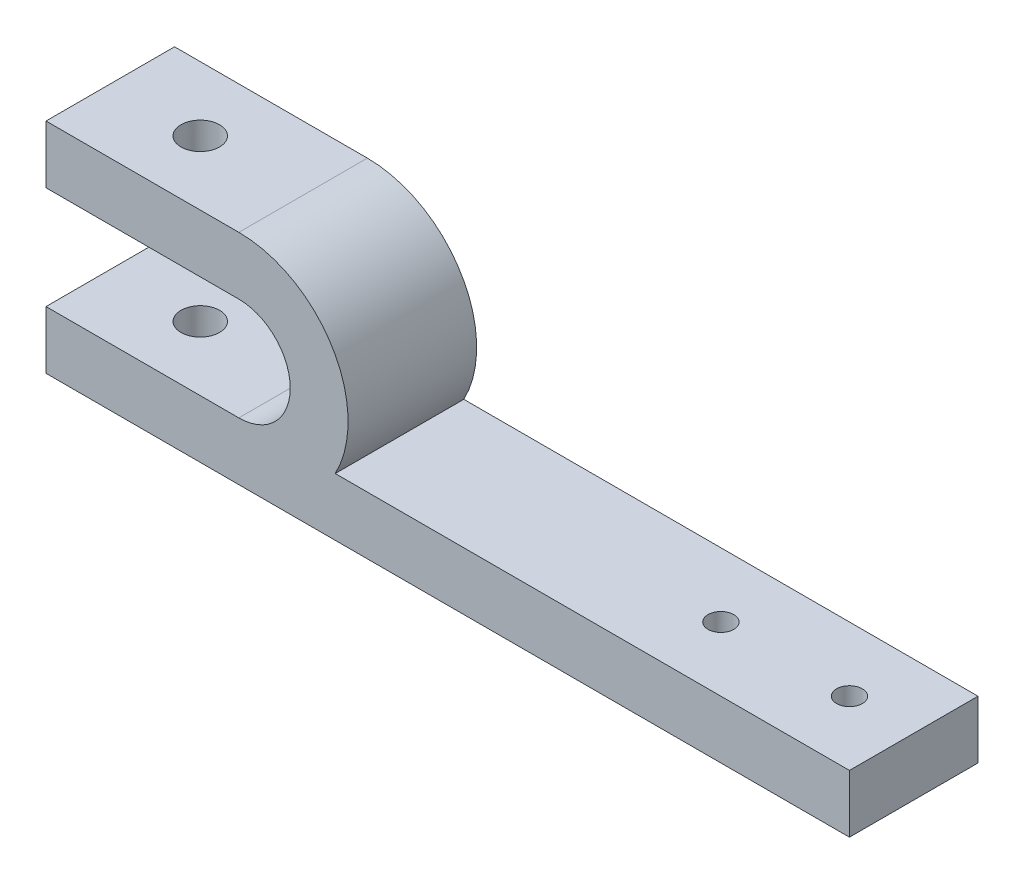
SolidWorks part; units mm, degrees
ref_plane "Alzado" through (0, 0, 0) normal (0, 0, 1) x (1, 0, 0)
ref_plane "Planta" through (0, 0, 0) normal (0, 1, 0) x (1, 0, 0)
ref_plane "Vista lateral" through (0, 0, 0) normal (1, 0, 0) x (0, 0, -1)
sketch "Croquis1" plane through (0, 0, 0) normal (0, 0, 1) x (1, 0, 0)
  line L0 (0, 4) -> (-15, 4)
  line L1 (-15, 4) -> (-15, 8.5)
  line L2 (-15, 8.5) -> (0, 8.5)
  line L3 (-15, -4) -> (0, -4)
  line L4 (47.5, -4) -> (47.5, -8.5)
  line L5 (47.5, -8.5) -> (-15, -8.5)
  line L6 (-15, -8.5) -> (-15, -4)
  line L7 (7.5, -4) -> (47.5, -4)
  arc A0 (0, -4) -> (0, 4) centre (0, 0) ccw
  arc A1 (7.5, -4) -> (0, 8.5) centre (0, 0) ccw
  dimension "D1" = 8
  dimension "D2" = 4.5
  dimension "D3" = 15
  dimension "D4" = 40
extrude "Saliente-Extruir1" add sketch "Croquis1" along normal blind 10
sketch "Croquis2" plane through (0, -8.5, 0) normal (0, -1, 0) x (1, 0, 0)
  line L0 (47.5, 10) -> (47.5, 0) construction
  line L1 (-15, 0) -> (47.5, 0) construction
  line L2 (-15, 10) -> (-15, 0) construction
  line L3 (-15, 10) -> (47.5, 10) construction
  circle A0 centre (42.5, 5) radius 1
  circle A1 centre (32.5, 5) radius 1
  circle A2 centre (-8, 5) radius 1.5
  dimension "D1" = 2
  dimension "D2" = 2
  dimension "D3" = 10
  dimension "D4" = 5
  dimension "D5" = 5
  dimension "D6" = 3
  dimension "D8" = 5
  dimension "D7" = 7
extrude "Cortar-Extruir1" cut sketch "Croquis2" against normal through all
